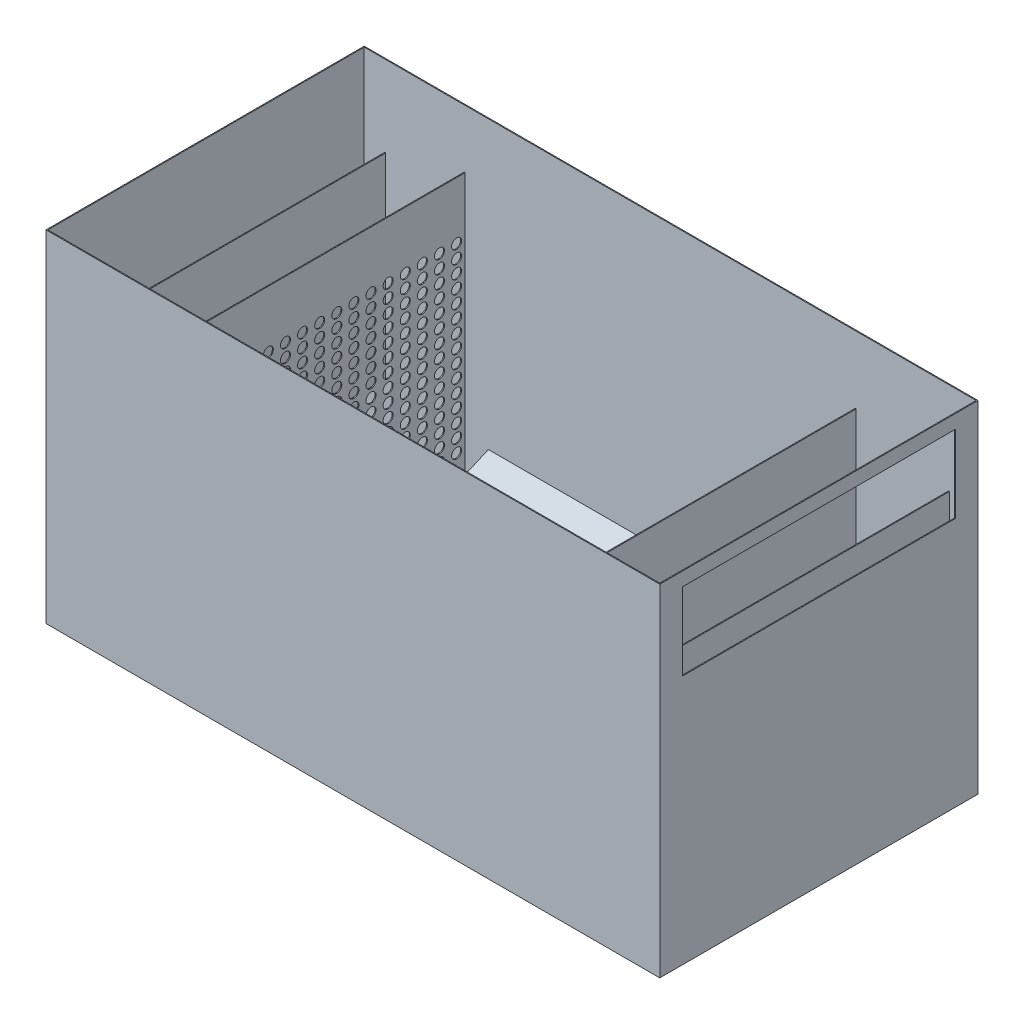
SolidWorks part; units mm, degrees
ref_plane "Спереди" through (0, 0, 0) normal (0, 0, 1) x (1, 0, 0)
ref_plane "Сверху" through (0, 0, 0) normal (0, 1, 0) x (1, 0, 0)
ref_plane "Справа" through (0, 0, 0) normal (1, 0, 0) x (0, 0, -1)
sketch "MASTER_FOOTPRINT" plane through (0, 0, 0) normal (0, 1, 0) x (1, 0, 0)
  line L1 (0, 0) -> (1350, 0)
  line L2 (0, 0) -> (0, 700)
  line L3 (0, 700) -> (1350, 700)
  line L4 (1350, 0) -> (1350, 700)
  dimension "D1" = 1350
  dimension "D2" = 700
extrude "BATH_BASE_PLATE" add sketch "MASTER_FOOTPRINT" along normal blind 750
shell "BATH_SHELL_2MM" thickness 2
sketch "Эскиз1" plane through (0, 0, 0) normal (1, 0, 0) x (0, 0, -1)
  circle A0 centre (350, 420) radius 50
extrude "INLET_D100_OPENING" cut sketch "Эскиз1" along normal blind 10
sketch "Эскиз2" plane through (0, 0, 0) normal (1, 0, 0) x (0, 0, -1)
  line L1 (80, 220) -> (620, 220)
  line L2 (80, 220) -> (80, 650)
  line L3 (80, 650) -> (620, 650)
  line L4 (620, 220) -> (620, 650)
extrude "INLET_IMPACT_BAFFLE" add sketch "Эскиз2" along normal blind 2 from offset 125 separate body
sketch "Эскиз3" plane through (0, 0, 0) normal (1, 0, 0) x (0, 0, -1)
  line L1 (30, 2) -> (670, 2)
  line L2 (30, 2) -> (30, 650)
  line L3 (30, 650) -> (670, 650)
  line L4 (670, 2) -> (670, 650)
  circle A0 centre (48.8235, 125) radius 11
  circle A1 centre (48.8235, 153.5) radius 11
  circle A2 centre (48.8235, 182) radius 11
  circle A3 centre (48.8235, 210.5) radius 11
  circle A4 centre (48.8235, 239) radius 11
  circle A5 centre (48.8235, 267.5) radius 11
  circle A6 centre (48.8235, 296) radius 11
  circle A7 centre (48.8235, 324.5) radius 11
  circle A8 centre (48.8235, 353) radius 11
  circle A9 centre (48.8235, 381.5) radius 11
  circle A10 centre (48.8235, 410) radius 11
  circle A11 centre (48.8235, 438.5) radius 11
  circle A12 centre (48.8235, 467) radius 11
  circle A13 centre (48.8235, 495.5) radius 11
  circle A14 centre (48.8235, 524) radius 11
  circle A15 centre (86.4706, 125) radius 11
  circle A16 centre (86.4706, 153.5) radius 11
  circle A17 centre (86.4706, 182) radius 11
  circle A18 centre (86.4706, 210.5) radius 11
  circle A19 centre (86.4706, 239) radius 11
  circle A20 centre (86.4706, 267.5) radius 11
  circle A21 centre (86.4706, 296) radius 11
  circle A22 centre (86.4706, 324.5) radius 11
  circle A23 centre (86.4706, 353) radius 11
  circle A24 centre (86.4706, 381.5) radius 11
  circle A25 centre (86.4706, 410) radius 11
  circle A26 centre (86.4706, 438.5) radius 11
  circle A27 centre (86.4706, 467) radius 11
  circle A28 centre (86.4706, 495.5) radius 11
  circle A29 centre (86.4706, 524) radius 11
  circle A30 centre (124.1176, 125) radius 11
  circle A31 centre (124.1176, 153.5) radius 11
  circle A32 centre (124.1176, 182) radius 11
  circle A33 centre (124.1176, 210.5) radius 11
  circle A34 centre (124.1176, 239) radius 11
  circle A35 centre (124.1176, 267.5) radius 11
  circle A36 centre (124.1176, 296) radius 11
  circle A37 centre (124.1176, 324.5) radius 11
  circle A38 centre (124.1176, 353) radius 11
  circle A39 centre (124.1176, 381.5) radius 11
  circle A40 centre (124.1176, 410) radius 11
  circle A41 centre (124.1176, 438.5) radius 11
  circle A42 centre (124.1176, 467) radius 11
  circle A43 centre (124.1176, 495.5) radius 11
  circle A44 centre (124.1176, 524) radius 11
  circle A45 centre (161.7647, 125) radius 11
  circle A46 centre (161.7647, 153.5) radius 11
  circle A47 centre (161.7647, 182) radius 11
  circle A48 centre (161.7647, 210.5) radius 11
  circle A49 centre (161.7647, 239) radius 11
  circle A50 centre (161.7647, 267.5) radius 11
  circle A51 centre (161.7647, 296) radius 11
  circle A52 centre (161.7647, 324.5) radius 11
  circle A53 centre (161.7647, 353) radius 11
  circle A54 centre (161.7647, 381.5) radius 11
  circle A55 centre (161.7647, 410) radius 11
  circle A56 centre (161.7647, 438.5) radius 11
  circle A57 centre (161.7647, 467) radius 11
  circle A58 centre (161.7647, 495.5) radius 11
  circle A59 centre (161.7647, 524) radius 11
  circle A60 centre (199.4118, 125) radius 11
  circle A61 centre (199.4118, 153.5) radius 11
  circle A62 centre (199.4118, 182) radius 11
  circle A63 centre (199.4118, 210.5) radius 11
  circle A64 centre (199.4118, 239) radius 11
  circle A65 centre (199.4118, 267.5) radius 11
  circle A66 centre (199.4118, 296) radius 11
  circle A67 centre (199.4118, 324.5) radius 11
  circle A68 centre (199.4118, 353) radius 11
  circle A69 centre (199.4118, 381.5) radius 11
  circle A70 centre (199.4118, 410) radius 11
  circle A71 centre (199.4118, 438.5) radius 11
  circle A72 centre (199.4118, 467) radius 11
  circle A73 centre (199.4118, 495.5) radius 11
  circle A74 centre (199.4118, 524) radius 11
  circle A75 centre (237.0588, 125) radius 11
  circle A76 centre (237.0588, 153.5) radius 11
  circle A77 centre (237.0588, 182) radius 11
  circle A78 centre (237.0588, 210.5) radius 11
  circle A79 centre (237.0588, 239) radius 11
  circle A80 centre (237.0588, 267.5) radius 11
  circle A81 centre (237.0588, 296) radius 11
  circle A82 centre (237.0588, 324.5) radius 11
  circle A83 centre (237.0588, 353) radius 11
  circle A84 centre (237.0588, 381.5) radius 11
  circle A85 centre (237.0588, 410) radius 11
  circle A86 centre (237.0588, 438.5) radius 11
  circle A87 centre (237.0588, 467) radius 11
  circle A88 centre (237.0588, 495.5) radius 11
  circle A89 centre (237.0588, 524) radius 11
  circle A90 centre (274.7059, 125) radius 11
  circle A91 centre (274.7059, 153.5) radius 11
  circle A92 centre (274.7059, 182) radius 11
  circle A93 centre (274.7059, 210.5) radius 11
  circle A94 centre (274.7059, 239) radius 11
  circle A95 centre (274.7059, 267.5) radius 11
  circle A96 centre (274.7059, 296) radius 11
  circle A97 centre (274.7059, 324.5) radius 11
  circle A98 centre (274.7059, 353) radius 11
  circle A99 centre (274.7059, 381.5) radius 11
  circle A100 centre (274.7059, 410) radius 11
  circle A101 centre (274.7059, 438.5) radius 11
  circle A102 centre (274.7059, 467) radius 11
  circle A103 centre (274.7059, 495.5) radius 11
  circle A104 centre (274.7059, 524) radius 11
  circle A105 centre (312.3529, 125) radius 11
  circle A106 centre (312.3529, 153.5) radius 11
  circle A107 centre (312.3529, 182) radius 11
  circle A108 centre (312.3529, 210.5) radius 11
  circle A109 centre (312.3529, 239) radius 11
  circle A110 centre (312.3529, 267.5) radius 11
  circle A111 centre (312.3529, 296) radius 11
  circle A112 centre (312.3529, 324.5) radius 11
  circle A113 centre (312.3529, 353) radius 11
  circle A114 centre (312.3529, 381.5) radius 11
  circle A115 centre (312.3529, 410) radius 11
  circle A116 centre (312.3529, 438.5) radius 11
  circle A117 centre (312.3529, 467) radius 11
  circle A118 centre (312.3529, 495.5) radius 11
  circle A119 centre (312.3529, 524) radius 11
  circle A120 centre (350, 125) radius 11
  circle A121 centre (350, 153.5) radius 11
  circle A122 centre (350, 182) radius 11
  circle A123 centre (350, 210.5) radius 11
  circle A124 centre (350, 239) radius 11
  circle A125 centre (350, 267.5) radius 11
  circle A126 centre (350, 296) radius 11
  circle A127 centre (350, 324.5) radius 11
  circle A128 centre (350, 353) radius 11
  circle A129 centre (350, 381.5) radius 11
  circle A130 centre (350, 410) radius 11
  circle A131 centre (350, 438.5) radius 11
  circle A132 centre (350, 467) radius 11
  circle A133 centre (350, 495.5) radius 11
  circle A134 centre (350, 524) radius 11
  circle A135 centre (387.6471, 125) radius 11
  circle A136 centre (387.6471, 153.5) radius 11
  circle A137 centre (387.6471, 182) radius 11
  circle A138 centre (387.6471, 210.5) radius 11
  circle A139 centre (387.6471, 239) radius 11
  circle A140 centre (387.6471, 267.5) radius 11
  circle A141 centre (387.6471, 296) radius 11
  circle A142 centre (387.6471, 324.5) radius 11
  circle A143 centre (387.6471, 353) radius 11
  circle A144 centre (387.6471, 381.5) radius 11
  circle A145 centre (387.6471, 410) radius 11
  circle A146 centre (387.6471, 438.5) radius 11
  circle A147 centre (387.6471, 467) radius 11
  circle A148 centre (387.6471, 495.5) radius 11
  circle A149 centre (387.6471, 524) radius 11
  circle A150 centre (425.2941, 125) radius 11
  circle A151 centre (425.2941, 153.5) radius 11
  circle A152 centre (425.2941, 182) radius 11
  circle A153 centre (425.2941, 210.5) radius 11
  circle A154 centre (425.2941, 239) radius 11
  circle A155 centre (425.2941, 267.5) radius 11
  circle A156 centre (425.2941, 296) radius 11
  circle A157 centre (425.2941, 324.5) radius 11
  circle A158 centre (425.2941, 353) radius 11
  circle A159 centre (425.2941, 381.5) radius 11
  circle A160 centre (425.2941, 410) radius 11
  circle A161 centre (425.2941, 438.5) radius 11
  circle A162 centre (425.2941, 467) radius 11
  circle A163 centre (425.2941, 495.5) radius 11
  circle A164 centre (425.2941, 524) radius 11
  circle A165 centre (462.9412, 125) radius 11
  circle A166 centre (462.9412, 153.5) radius 11
  circle A167 centre (462.9412, 182) radius 11
  circle A168 centre (462.9412, 210.5) radius 11
  circle A169 centre (462.9412, 239) radius 11
  circle A170 centre (462.9412, 267.5) radius 11
  circle A171 centre (462.9412, 296) radius 11
  circle A172 centre (462.9412, 324.5) radius 11
  circle A173 centre (462.9412, 353) radius 11
  circle A174 centre (462.9412, 381.5) radius 11
  circle A175 centre (462.9412, 410) radius 11
  circle A176 centre (462.9412, 438.5) radius 11
  circle A177 centre (462.9412, 467) radius 11
  circle A178 centre (462.9412, 495.5) radius 11
  circle A179 centre (462.9412, 524) radius 11
  circle A180 centre (500.5882, 125) radius 11
  circle A181 centre (500.5882, 153.5) radius 11
  circle A182 centre (500.5882, 182) radius 11
  circle A183 centre (500.5882, 210.5) radius 11
  circle A184 centre (500.5882, 239) radius 11
  circle A185 centre (500.5882, 267.5) radius 11
  circle A186 centre (500.5882, 296) radius 11
  circle A187 centre (500.5882, 324.5) radius 11
  circle A188 centre (500.5882, 353) radius 11
  circle A189 centre (500.5882, 381.5) radius 11
  circle A190 centre (500.5882, 410) radius 11
  circle A191 centre (500.5882, 438.5) radius 11
  circle A192 centre (500.5882, 467) radius 11
  circle A193 centre (500.5882, 495.5) radius 11
  circle A194 centre (500.5882, 524) radius 11
  circle A195 centre (538.2353, 125) radius 11
  circle A196 centre (538.2353, 153.5) radius 11
  circle A197 centre (538.2353, 182) radius 11
  circle A198 centre (538.2353, 210.5) radius 11
  circle A199 centre (538.2353, 239) radius 11
  circle A200 centre (538.2353, 267.5) radius 11
  circle A201 centre (538.2353, 296) radius 11
  circle A202 centre (538.2353, 324.5) radius 11
  circle A203 centre (538.2353, 353) radius 11
  circle A204 centre (538.2353, 381.5) radius 11
  circle A205 centre (538.2353, 410) radius 11
  circle A206 centre (538.2353, 438.5) radius 11
  circle A207 centre (538.2353, 467) radius 11
  circle A208 centre (538.2353, 495.5) radius 11
  circle A209 centre (538.2353, 524) radius 11
  circle A210 centre (575.8824, 125) radius 11
  circle A211 centre (575.8824, 153.5) radius 11
  circle A212 centre (575.8824, 182) radius 11
  circle A213 centre (575.8824, 210.5) radius 11
  circle A214 centre (575.8824, 239) radius 11
  circle A215 centre (575.8824, 267.5) radius 11
  circle A216 centre (575.8824, 296) radius 11
  circle A217 centre (575.8824, 324.5) radius 11
  circle A218 centre (575.8824, 353) radius 11
  circle A219 centre (575.8824, 381.5) radius 11
  circle A220 centre (575.8824, 410) radius 11
  circle A221 centre (575.8824, 438.5) radius 11
  circle A222 centre (575.8824, 467) radius 11
  circle A223 centre (575.8824, 495.5) radius 11
  circle A224 centre (575.8824, 524) radius 11
  circle A225 centre (613.5294, 125) radius 11
  circle A226 centre (613.5294, 153.5) radius 11
  circle A227 centre (613.5294, 182) radius 11
  circle A228 centre (613.5294, 210.5) radius 11
  circle A229 centre (613.5294, 239) radius 11
  circle A230 centre (613.5294, 267.5) radius 11
  circle A231 centre (613.5294, 296) radius 11
  circle A232 centre (613.5294, 324.5) radius 11
  circle A233 centre (613.5294, 353) radius 11
  circle A234 centre (613.5294, 381.5) radius 11
  circle A235 centre (613.5294, 410) radius 11
  circle A236 centre (613.5294, 438.5) radius 11
  circle A237 centre (613.5294, 467) radius 11
  circle A238 centre (613.5294, 495.5) radius 11
  circle A239 centre (613.5294, 524) radius 11
  circle A240 centre (651.1765, 125) radius 11
  circle A241 centre (651.1765, 153.5) radius 11
  circle A242 centre (651.1765, 182) radius 11
  circle A243 centre (651.1765, 210.5) radius 11
  circle A244 centre (651.1765, 239) radius 11
  circle A245 centre (651.1765, 267.5) radius 11
  circle A246 centre (651.1765, 296) radius 11
  circle A247 centre (651.1765, 324.5) radius 11
  circle A248 centre (651.1765, 353) radius 11
  circle A249 centre (651.1765, 381.5) radius 11
  circle A250 centre (651.1765, 410) radius 11
  circle A251 centre (651.1765, 438.5) radius 11
  circle A252 centre (651.1765, 467) radius 11
  circle A253 centre (651.1765, 495.5) radius 11
  circle A254 centre (651.1765, 524) radius 11
extrude "DISTRIBUTOR_D22" add sketch "Эскиз3" along normal blind 2 from offset 250 separate body
sketch "Эскиз4" plane through (0, 0, 0) normal (1, 0, 0) x (0, 0, -1)
  line L1 (50, 320) -> (650, 320)
  line L2 (50, 320) -> (50, 650)
  line L3 (50, 650) -> (650, 650)
  line L4 (650, 320) -> (650, 650)
extrude "OUTLET_SUBMERGED_BAFFLE" add sketch "Эскиз4" along normal blind 2 from offset 1130 separate body
sketch "Эскиз5" plane through (0, 0, 0) normal (1, 0, 0) x (0, 0, -1)
  line L1 (5, 2) -> (695, 2)
  line L2 (5, 2) -> (5, 550)
  line L3 (5, 550) -> (695, 550)
  line L4 (695, 2) -> (695, 550)
extrude "OVERFLOW_WEIR_Z550" add sketch "Эскиз5" along normal blind 2 from offset 1290 separate body
sketch "Эскиз6" plane through (0, 0, 0) normal (1, 0, 0) x (0, 0, -1)
  line L1 (50, 550) -> (650, 550)
  line L2 (50, 550) -> (50, 720)
  line L3 (50, 720) -> (650, 720)
  line L4 (650, 550) -> (650, 720)
extrude "OUTLET_WEIR_SLOT_W600" cut sketch "Эскиз6" along normal blind 10 from offset 1345
sketch "Эскиз7" plane through (0, 0, 0) normal (1, 0, 0) x (0, 0, -1)
  line L0 (2, -1) -> (2, 120)
  line L1 (2, 120) -> (280, -1)
  line L2 (280, -1) -> (2, -1)
  line L3 (698, -1) -> (698, 120)
  line L4 (698, 120) -> (420, -1)
  line L5 (420, -1) -> (698, -1)
extrude "SLOPED_SEDIMENT_FLOOR" add sketch "Эскиз7" along normal blind 825 from offset 275
sketch3d "SCREW_AXIS_30DEG_REFERENCE"
  line L0 (400, 70, -350) -> (1450, 676.2178, -350)
equation "\"AI_Q_Peak\"= 0.006"
equation "\"AI_B_Bath\"= 700"
equation "\"AI_L_Settle\"= 900"
equation "\"AI_L_Inlet\"= 250"
equation "\"AI_L_Outlet\"= 200"
equation "\"AI_L_Bath\"= 1350"
equation "\"AI_H_Water\"= 550"
equation "\"AI_H_Freeboard\"= 200"
equation "\"AI_H_Bath\"= 750"
equation "\"AI_Shell_Thickness\"= 2"
equation "\"AI_Inlet_DN\"= 100"
equation "\"AI_Weir_Width\"= 600"
equation "\"AI_Inlet_Baffle_Offset\"= 125"
equation "\"AI_Distributor_Open_Area\"= 0.28"
equation "\"AI_Distributor_Hole_Dia\"= 22"
equation "\"AI_Distributor_Blind_Zone\"= 110"
equation "\"AI_Outlet_Baffle_Depth\"= 250"
equation "\"AI_Screw_Diameter\"= 100"
equation "\"AI_Screw_Pitch\"= 100"
equation "\"AI_Screw_Angle\"= 30"
equation "\"AI_Screw_Rpm\"= 15"
equation "\"AI_Screw_Clearance\"= 5"
equation "\"AI_Liner_Thickness\"= 5"
equation "\"AI_Discharge_Height\"= 650"
equation "\"AI_Frame_Height\"= 500"
equation "\"D1@MASTER_FOOTPRINT\" = \"AI_L_Bath\""
equation "\"D2@MASTER_FOOTPRINT\" = \"AI_B_Bath\""
equation "\"D1@BATH_BASE_PLATE\" = \"AI_H_Bath\""
